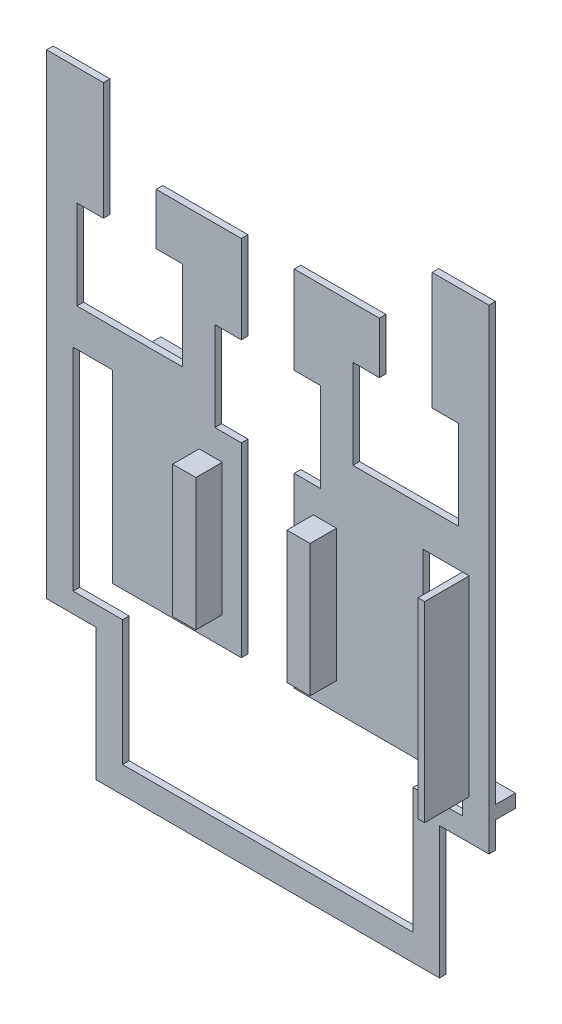
SolidWorks part; units mm, degrees
ref_plane "Front Plane" through (0, 0, 0) normal (0, 0, 1) x (1, 0, 0)
ref_plane "Top Plane" through (0, 0, 0) normal (0, 1, 0) x (1, 0, 0)
ref_plane "Right Plane" through (0, 0, 0) normal (1, 0, 0) x (0, 0, -1)
sketch "Sketch1" plane through (0, 0, 0) normal (0, 0, 1) x (1, 0, 0)
  line L0 (33.5, 0) -> (33.5, 72)
  line L1 (33.5, 0) -> (-33.5, 0)
  line L2 (0, 0) -> (0, 72)
  line L3 (33.5, 72) -> (-33.5, 72)
  line L4 (-33.5, 0) -> (-33.5, 72)
  line L6 (-26, 0) -> (26, 0)
  line L7 (-26, 0) -> (-26, -20)
  line L8 (-26, -20) -> (26, -20)
  line L9 (26, 0) -> (26, -20)
  dimension "D1" = 67
  dimension "D2" = 72
  dimension "D3" = 20
  dimension "D4" = 26
  dimension "D5" = 52
extrude "Boss-Extrude1" add sketch "Sketch1" along normal blind 1 contours L4 L1 L2 L3 | L0 L3 L2 L1 | L9 L1 L7 L8
sketch "Sketch2" plane through (0, 0, 1) normal (0, 0, 1) x (1, 0, 0)
  line L0 (33.5, 72) -> (-33.5, 72) construction
  line L1 (22, -16) -> (-22, -16)
  line L2 (22, -16) -> (22, 3)
  line L3 (22, 7) -> (4, 7)
  line L4 (-22, -16) -> (-22, 3)
  line L6 (4, 7) -> (4, 35.2)
  line L8 (-4, 7) -> (-4, 35.2)
  line L9 (8, 35.2) -> (4, 35.2)
  line L10 (8, 35.2) -> (8, 48.7)
  line L11 (8, 48.7) -> (4, 48.7)
  line L12 (-8, 35.2) -> (-8, 48.7)
  line L13 (28.9, 40.7) -> (12.9, 40.7)
  line L14 (28.9, 40.7) -> (28.9, 54.2)
  line L15 (28.9, 54.2) -> (12.9, 54.2)
  line L16 (12.9, 40.7) -> (12.9, 54.2)
  line L17 (24.9, 54.2) -> (16.9, 54.2)
  line L18 (24.9, 54.2) -> (24.9, 72)
  line L19 (24.9, 72) -> (16.9, 72)
  line L20 (16.9, 54.2) -> (16.9, 62)
  line L21 (-26, -20) -> (26, -20) construction
  line L30 (-4, 35.2) -> (-8, 35.2)
  line L31 (-4, 7) -> (-23.5, 7)
  line L32 (26, 0) -> (26, -20) construction
  line L33 (-4, 48.7) -> (-8, 48.7)
  line L34 (-24.9, 72) -> (-16.9, 72)
  line L35 (-16.9, 54.2) -> (-16.9, 62)
  line L36 (-24.9, 54.2) -> (-16.9, 54.2)
  line L37 (-24.9, 54.2) -> (-24.9, 72)
  line L38 (-28.9, 54.2) -> (-12.9, 54.2)
  line L39 (-12.9, 40.7) -> (-12.9, 54.2)
  line L40 (-28.9, 40.7) -> (-12.9, 40.7)
  line L41 (-28.9, 40.7) -> (-28.9, 54.2)
  line L43 (4, 48.7) -> (4, 62)
  line L44 (4, 72) -> (-4, 72)
  line L45 (-4, 33.6206) -> (-4, 35.2)
  line L46 (-4, 48.7) -> (-4, 62)
  line L47 (16.9, 62) -> (4, 62)
  line L48 (-29.5, 3) -> (-22, 3)
  line L49 (-29.5, 3) -> (-29.5, 35)
  line L50 (-29.5, 35) -> (-23.5, 35)
  line L51 (-23.5, 7) -> (-23.5, 35)
  line L52 (-26, 0) -> (-33.5, 0) construction
  line L53 (0, 0) -> (0, 81.8482) construction
  line L54 (29.5, 35) -> (23.5, 35)
  line L55 (29.5, 3) -> (22, 3)
  line L56 (4, 7) -> (23.5, 7)
  line L57 (23.5, 7) -> (23.5, 35)
  line L58 (29.5, 3) -> (29.5, 35)
  line L59 (-4, 62) -> (-16.9, 62)
  line L60 (16.9, 72) -> (-16.9, 72)
  dimension "D1" = 34
  dimension "D2" = 55.2
  dimension "D3" = 13.5
  dimension "D4" = 16
  dimension "D5" = 19.5
  dimension "D6" = 4
  dimension "D7" = 32
  dimension "D8" = 18
  dimension "D9" = 23
  dimension "D10" = 4
  dimension "D11" = 8
  dimension "D12" = 74.2
  dimension "D13" = 13.1
  dimension "D14" = 16
  dimension "D15" = 13.5
  dimension "D16" = 4
  dimension "D17" = 0
  dimension "D18" = 8
  dimension "D19" = 4
  dimension "D20" = 6
  dimension "D21" = 3
  dimension "D22" = 10
extrude "Cut-Extrude2" cut sketch "Sketch2" against normal blind 1
sketch "Sketch5" plane through (0, 0, 1) normal (0, 0, 1) x (1, 0, 0)
  line L0 (29.5, 3) -> (22, 3) construction
  line L1 (30.5, 6) -> (29.5, 6)
  line L2 (30.5, 6) -> (30.5, 35)
  line L3 (30.5, 35) -> (29.5, 35)
  line L4 (29.5, 6) -> (29.5, 35)
  dimension "D1" = 3
  dimension "D2" = 1
extrude "Boss-Extrude3" add sketch "Sketch5" along normal blind 6.75
sketch "Sketch6" plane through (0, 0, 1) normal (0, 0, 1) x (1, 0, 0)
  line L0 (-26, -20) -> (26, -20) construction
  line L1 (6.9, 11.2) -> (10.4, 11.2)
  line L2 (6.9, 11.2) -> (6.9, 31.2)
  line L3 (6.9, 31.2) -> (10.4, 31.2)
  line L4 (10.4, 11.2) -> (10.4, 31.2)
  line L5 (-26, 0) -> (-26, -20) construction
  point P6 (0, 0)
  dimension "D1" = 3.5
  dimension "D2" = 20
  dimension "D3" = 31.2
  dimension "D4" = 36.4
extrude "Boss-Extrude4" add sketch "Sketch6" along normal blind 4
mirror "Mirror1" about plane through (0, 0, 0) normal (1, 0, 0) of "Boss-Extrude4"
sketch "Sketch7" plane through (0, 0, 0) normal (0, 0, -1) x (-1, 0, 0)
  line L0 (26, 0) -> (26, -20) construction
  line L1 (14.2, 29) -> (16.2, 29)
  line L2 (14.2, 29) -> (14.2, 39)
  line L3 (14.2, 39) -> (16.2, 39)
  line L4 (16.2, 29) -> (16.2, 37)
  line L5 (16.2, 39) -> (20.2, 39)
  line L7 (16.2, 37) -> (20.2, 37)
  line L8 (20.2, 39) -> (20.2, 37)
  line L9 (26, -20) -> (-26, -20) construction
  line L10 (-33.5, 0) -> (-33.5, 72) construction
  line L11 (-33.5, 4) -> (-29.5, 4)
  line L12 (-33.5, 4) -> (-33.5, 6)
  line L13 (-33.5, 6) -> (-29.5, 6)
  line L14 (-29.5, 4) -> (-29.5, 6)
  line L15 (-29.5, 3) -> (-29.5, 35) construction
  line L16 (-33.5, 0) -> (-26, 0) construction
  line L18 (11, 30) -> (13, 30)
  line L19 (11, 30) -> (11, 20)
  line L20 (11, 20) -> (13, 20)
  line L21 (13, 30) -> (13, 20)
  point P25 (12, 20)
  dimension "D1" = 9.8
  dimension "D2" = 57
  dimension "D3" = 2
  dimension "D4" = 2
  dimension "D5" = 10
  dimension "D6" = 10
  dimension "D7" = 0
  dimension "D8" = 0
  dimension "D9" = 2
  dimension "D10" = 6
  dimension "D11" = 6
  dimension "D12" = 15
  dimension "D13" = 2
  dimension "D14" = 40
extrude "Boss-Extrude5" add sketch "Sketch7" along normal blind 3
